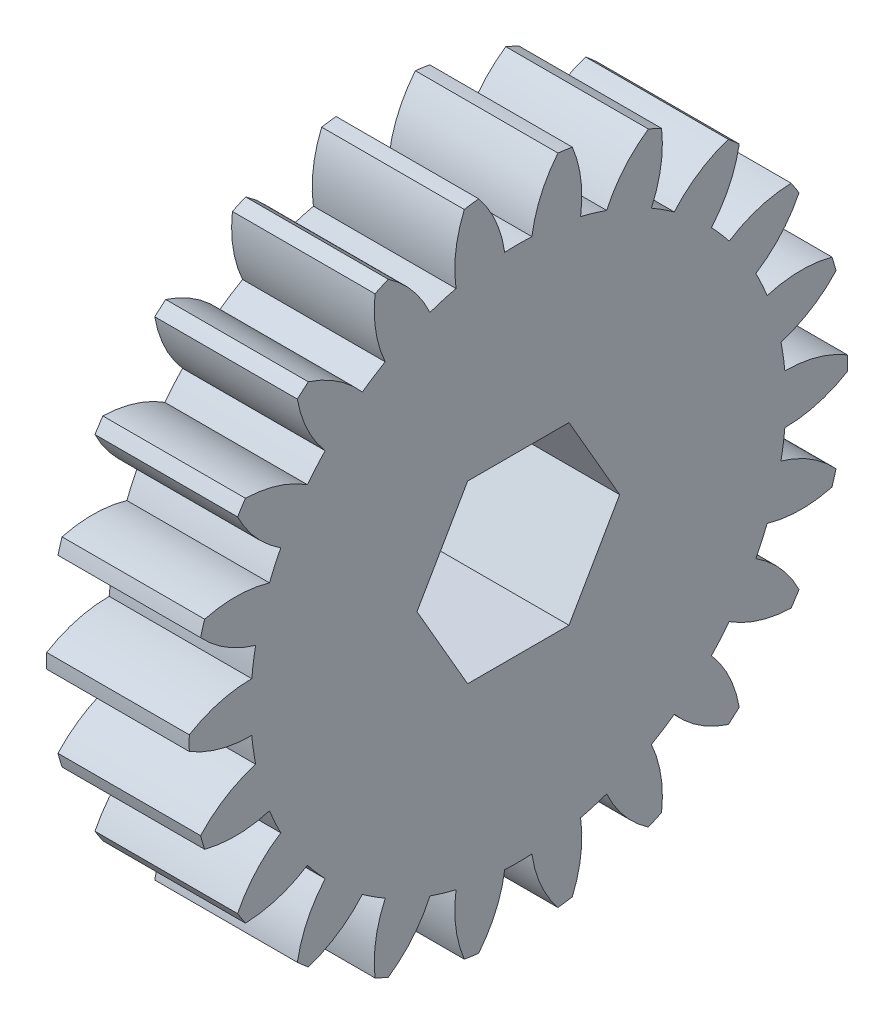
SolidWorks part; units mm, degrees
ref_plane "Plane1" through (0, 0, 0) normal (0, 0, 1) x (1, 0, 0)
ref_plane "Plane2" through (0, 0, 0) normal (0, 1, 0) x (1, 0, 0)
ref_plane "Plane3" through (0, 0, 0) normal (1, 0, 0) x (0, 0, -1)
sketch "HoldingSke" plane through (0, 0, 0) normal (0, 1, 0) x (1, 0, 0)
  line L0 (0, 0) -> (471.0094, -190.3001)
  line L1 (-15, 0) -> (100, 0) construction
  line L2 (0, 0) -> (-2.1039, 2.3779)
  line L3 (0, 0) -> (-11.863, 4.5341)
  line L4 (0, 0) -> (8.0072, 3.2351)
  line L5 (0, 0) -> (-47.5972, -17.7524)
  line L6 (0, 0) -> (-5.4745, -3.6936)
  line L7 (-2.1039, 2.3779) -> (8.8308, 51.9871)
  line L8 (-76.2, 54.61) -> (-75.184, 54.61)
  line L9 (-71.009, 38.7566) -> (-53.1078, 45.2721)
  line L10 (-76.2, 71.12) -> (104.1128, 71.12)
  line L11 (0, 0) -> (-6.604, 0)
  line L12 (-76.2, 101.6) -> (-76.1492, 101.6)
  line L13 (24.9733, 27.94) -> (52.9518, 28.4284)
  line L14 (24.9733, 27.94) -> (25.0241, 27.9398)
  line L15 (24.9733, 27.94) -> (100.4021, 29.52)
  circle A0 centre (0, 0) radius 0.5
  circle A1 centre (0, 0) radius 12.3952
  circle A2 centre (0, 0) radius 38.1
  circle A3 centre (0, 0) radius 0.5
  dimension "MHD" = 24.7904
  dimension "Hub_dia" = 76.2
  dimension "Bore" = 1
  dimension "MBD" = 1
  dimension "Num_teeth" = 22
  dimension "Pitch" = 508
  dimension "Overall_len" = 50.8
  dimension "Show_teeth" = 22
  dimension "Thickness" = 6.604
  dimension "OAL" = 50.8001
  dimension "T_dim" = 1.016
  dimension "Ap" = 20
  dimension "H" = 19.05
  dimension "Pitch_radius" = 180.3128
  dimension "Width" = 6.604
  dimension "Backlash" = 0.0508
  dimension "Addendum_fac" = 1
  dimension "Dedendum_fac" = 1.2
  dimension "Clearance_fac" = 0.2
  dimension "Dedendum_add" = 0.0508
sketch "BasProSke" plane through (0, 0, 0) normal (0, 1, 0) x (1, 0, 0)
  line L0 (-10, 0) -> (60, 0) construction
  line L1 (0, 0) -> (0, 15.24)
  line L2 (0, 0) -> (6.604, 0)
  line L3 (6.604, 0) -> (6.604, 15.24)
  line L4 (6.604, 15.24) -> (0, 15.24)
  dimension "Thickness" = 6.604
  dimension "Diameter" = 30.48
revolve "Base-Revolve" add sketch "BasProSke" angle 360 about L0
sketch "TooCutSke" plane through (0, 0, 0) normal (1, 0, 0) x (0, 0, -1)
  line L1 (0, 0) -> (0, 107) construction
  line L2 (0, 0) -> (-1.0855, 13.9278) construction
  line L3 (0, 0) -> (-3.9679, 27.5972) construction
  line L4 (-1.0855, 13.9278) -> (-1.9839, 13.7986) construction
  arc A0 (0.6295, 12.3792) -> (-0.6295, 12.3792) centre (0, 0) ccw
  arc A1 (1.855, 15.1523) -> (-1.855, 15.1523) centre (0, 0) ccw
  circle A2 centre (0, 0) radius 13.97 construction
  circle A3 centre (0, 0) radius 13.1275 construction
  arc A4 (-0.6295, 12.3792) -> (-1.855, 15.1523) centre (-6.1617, 11.5916) ccw
  arc A5 (1.855, 15.1523) -> (0.6295, 12.3792) centre (6.1617, 11.5916) ccw
  dimension "Root_dia" = 24.7904
  dimension "Overcut_dia" = 30.5308
  dimension "Pitch_dia" = 27.94
  dimension "Base_dia" = 26.255
  dimension "Flank_rad" = 5.588
  dimension "Half_ang" = 8.182
  dimension "Half_CT" = 0.9077
extrude "ToothCut" cut sketch "TooCutSke" along normal through all
fillet "Breaks" [suppressed] radius 0.0254
fillet "RootFillets" [suppressed] radius 0.3048
pattern_circular "TeethCuts" count 22 every 16.364 about axis through (-10, 0, 0) along (1, 0, 0) of "ToothCut", "RootFillets", "Breaks"
sketch "HubNeaOneSke" plane through (0, 0, 0) normal (-1, 0, 0) x (0, 0, 1)
  circle A0 centre (0, 0) radius 12.3952
  dimension "Diameter" = 24.7904
extrude "HubNearOne" [suppressed] add sketch "HubNeaOneSke" along normal blind 44.1961
sketch "HubNeaBotSke" plane through (0, 0, 0) normal (-1, 0, 0) x (0, 0, 1)
  circle A0 centre (0, 0) radius 12.3952
  dimension "Diameter" = 24.7904
extrude "HubNearBoth" [suppressed] add sketch "HubNeaBotSke" along normal blind 22.098
ref_plane "FarPln" through (6.604, 0, 0) normal (1, 0, 0) x (0, 0, -1)
sketch "HubFarSke" plane through (6.604, 0, 0) normal (1, 0, 0) x (0, 0, -1)
  circle A0 centre (0, 0) radius 12.3952
  dimension "Diameter" = 24.7904
extrude "HubFar" [suppressed] add sketch "HubFarSke" along normal blind 22.098
sketch "BorSke" plane through (0, 0, 0) normal (1, 0, 0) x (0, 0, -1)
  circle A0 centre (0, 0) radius 0.5
  dimension "Diameter" = 1
extrude "Bore" cut sketch "BorSke" along normal mid plane 101.6001
sketch "KeySke" plane through (0, 0, 0) normal (1, 0, 0) x (0, 0, -1)
  line L0 (-0.127, 0) -> (-0.127, 0.516)
  line L1 (-0.127, 0.516) -> (0.127, 0.516)
  line L2 (0.127, 0.516) -> (0.127, 0)
  line L3 (0, 0) -> (0, 34) construction
  line L4 (-0.127, 0) -> (0.127, 0)
  dimension "Offset" = 0.516
  dimension "Width" = 0.254
extrude "Keyway" [suppressed] cut sketch "KeySke" along normal mid plane 101.6001
pattern_circular "Keyway2" [suppressed] count 2 every 90 about axis through (-10, 0, 0) along (1, 0, 0)
sketch "Sketch1" plane through (0, 0, 0) normal (-1, 0, 0) x (0, 0, 1)
  circle A0 centre (0, 0) radius 6.985
  dimension "D1" = 13.97
extrude "Boss-Extrude1" add sketch "Sketch1" along normal blind 2.286
sketch "Sketch2" plane through (6.604, 0, 0) normal (1, 0, 0) x (0, 0, -1)
  line L1 (2.3464, 4.064) -> (-2.3464, 4.064)
  line L2 (-2.3464, 4.064) -> (-4.6927, 0)
  line L3 (-4.6927, 0) -> (-2.3464, -4.064)
  line L4 (-2.3464, -4.064) -> (2.3464, -4.064)
  line L5 (2.3464, -4.064) -> (4.6927, 0)
  line L6 (4.6927, 0) -> (2.3464, 4.064)
  circle A0 centre (0, 0) radius 4.064 construction
  dimension "D1" = 8.128
extrude "Cut-Extrude1" cut sketch "Sketch2" against normal through all
equation "' \"Pitch@HoldingSke\" = 4"
equation "' \"Num_teeth@HoldingSke\" = 12"
equation "' \"Ap@HoldingSke\" =  20"
equation "' \"Ap@HoldingSke\" = 20"
equation "' \"Width@HoldingSke\" = 0.5"
equation "' \"Hub_dia@HoldingSke\"= 1"
equation "' \"Hub_dia@HoldingSke\" = 1"
equation "' \"Overall_len@HoldingSke\" = 1.0"
equation "' \"Bore@HoldingSke\" = 0.75"
equation "' \"T_dim@HoldingSke\" = 0.85"
equation "' \"Width@KeySke\" = 0.25"
equation "' \"Show_teeth@HoldingSke\" = 13"
equation "' \"Backlash@HoldingSke\" = 0.009"
equation "' \"Addendum_fac@HoldingSke\" = 1.0"
equation "' \"Dedendum_fac@HoldingSke\" = 1.25"
equation "' \"Dedendum_add@HoldingSke\" = 0.00005"
equation "' \"Clearance_fac@HoldingSke\" = 0.25"
equation "' \"Pitch@HoldingSke\" = 0.5"
equation "' \"Num_teeth@HoldingSke\" = 23"
equation "' \"Show_teeth@HoldingSke\" = 23"
equation "' \"Backlash@HoldingSke\" = 0.0375"
equation "\"Overcut_dia@TooCutSke\" = (\"Num_teeth@HoldingSke\" + 2 * \"Addendum_fac@HoldingSke\") / \"Pitch@HoldingSke\" + 0.002"
equation "\"Pitch_dia@TooCutSke\" = \"Num_teeth@HoldingSke\" / \"Pitch@HoldingSke\""
equation "\"Base_dia@TooCutSke\" = \"Num_teeth@HoldingSke\" / \"Pitch@HoldingSke\" * cos((\"Ap@HoldingSke\"  * 3.14159265 / 180))"
equation "\"Root_dia@TooCutSke\" = (\"Num_teeth@HoldingSke\" + 2) / \"Pitch@HoldingSke\" - 2 * (\"Addendum_fac@HoldingSke\" + \"Dedendum_fac@HoldingSke\") / \"Pitch@HoldingSke\" - \"Dedendum_add@HoldingSke\" * 2"
equation "\"Half_ang@TooCutSke\" = 180 / \"Num_teeth@HoldingSke\""
equation "\"Half_CT@TooCutSke\" = \"Num_teeth@HoldingSke\" / \"Pitch@HoldingSke\" * sin((3.14159265 / 2 / \"Num_teeth@HoldingSke\")) / 2 - 7 * \"Backlash@HoldingSke\" / 4"
equation "\"Flank_rad@TooCutSke\" = \"Num_teeth@HoldingSke\" / \"Pitch@HoldingSke\" / 5"
equation "\"Radius@RootFillets\" = \"Clearance_fac@HoldingSke\" / \"Pitch@HoldingSke\" + \"Dedendum_add@HoldingSke\""
equation "\"Break_rad@Breaks\" = 0.02 / \"Pitch@HoldingSke\""
equation "\"Thickness@HoldingSke\" = \"Width@HoldingSke\""
equation "\"OAL@HoldingSke\" = \"Thickness@HoldingSke\""
equation "\"MHD@HoldingSke\" = (\"Num_teeth@HoldingSke\" + 2) / \"Pitch@HoldingSke\" - 2 * (\"Addendum_fac@HoldingSke\" + \"Dedendum_fac@HoldingSke\")  / \"Pitch@HoldingSke\" - \"Dedendum_add@HoldingSke\" * 2"
equation "\"MBD@HoldingSke\" = (\"Num_teeth@HoldingSke\" + 2) / \"Pitch@HoldingSke\" - 2 * (\"Addendum_fac@HoldingSke\" + \"Dedendum_fac@HoldingSke\")  / \"Pitch@HoldingSke\" - \"Dedendum_add@HoldingSke\" * 2 - 0.002"
equation "\"MHD@HoldingSke\" = ((sgn( \"MHD@HoldingSke\" - \"Hub_dia@HoldingSke\" )-1)*( \"MHD@HoldingSke\" - \"Hub_dia@HoldingSke\" ))/-2+ \"Hub_dia@HoldingSke\""
equation "\"MBD@HoldingSke\" = ((sgn( \"MBD@HoldingSke\" - \"Bore@HoldingSke\" )-1)*( \"MBD@HoldingSke\" - \"Bore@HoldingSke\" ))/-2+ \"Bore@HoldingSke\""
equation "\"OAL@HoldingSke\" = ((sgn( \"OAL@HoldingSke\" - \"Overall_len@HoldingSke\" )+1)*( \"OAL@HoldingSke\" - \"Overall_len@HoldingSke\" ))/2 + \"Overall_len@HoldingSke\" + 0.000002"
equation "\"Num_teeth@TeethCuts\" = int( \"Show_teeth@HoldingSke\" ) + 1"
equation "\"Num_teeth@TeethCuts\" = ((sgn( \"Num_teeth@TeethCuts\" - \"Num_teeth@HoldingSke\" )-1)*( \"Num_teeth@TeethCuts\" - \"Num_teeth@HoldingSke\" ))/-2+ \"Num_teeth@HoldingSke\""
equation "\"Num_teeth@TeethCuts\" = ((sgn( \"Num_teeth@TeethCuts\" - 2.0)+1)*( \"Num_teeth@TeethCuts\" - 2.0))/2 +2.0"
equation "\"Angle@TeethCuts\" = 360.0 / \"Num_teeth@HoldingSke\""
equation "\"Diameter@BasProSke\" = (\"Num_teeth@HoldingSke\" + 2 * \"Addendum_fac@HoldingSke\") / \"Pitch@HoldingSke\""
equation "\"Thickness@BasProSke\"  = \"Thickness@HoldingSke\""
equation "' \"Fillet_rad@BasProSke\" =  \"Thickness@HoldingSke\" * 0.05"
equation "' \"Fillet_rad@BasProSke\" = \"Thickness@HoldingSke\" * 0.05"
equation "\"MHD@HoldingSke\" = ((sgn( \"MHD@HoldingSke\" - \"Root_dia@TooCutSke\" )-1)*( \"MHD@HoldingSke\" - \"Root_dia@TooCutSke\" ))/-2+ \"Root_dia@TooCutSke\""
equation "\"Diameter@HubNeaOneSke\" = \"MHD@HoldingSke\""
equation "\"Length@HubNearOne\" = \"OAL@HoldingSke\" - \"Thickness@BasProSke\""
equation "\"Diameter@HubNeaBotSke\" = \"MHD@HoldingSke\""
equation "\"Length@HubNearBoth\" = ( \"OAL@HoldingSke\" - \"Thickness@BasProSke\" ) / 2.0"
equation "\"Thickness@FarPln\" = \"Thickness@BasProSke\""
equation "\"Diameter@HubFarSke\" = \"MHD@HoldingSke\""
equation "\"Length@HubFar\" = ( \"OAL@HoldingSke\" - \"Thickness@BasProSke\" ) / 2.0"
equation "\"Diameter@BorSke\" = \"MBD@HoldingSke\""
equation "\"D1@Bore\" = \"OAL@HoldingSke\" * 2.0"
equation "\"D1@Keyway\" = \"OAL@HoldingSke\" * 2.0"
equation "\"Offset@KeySke\" = \"T_dim@HoldingSke\" - \"MBD@HoldingSke\" / 2.0"
